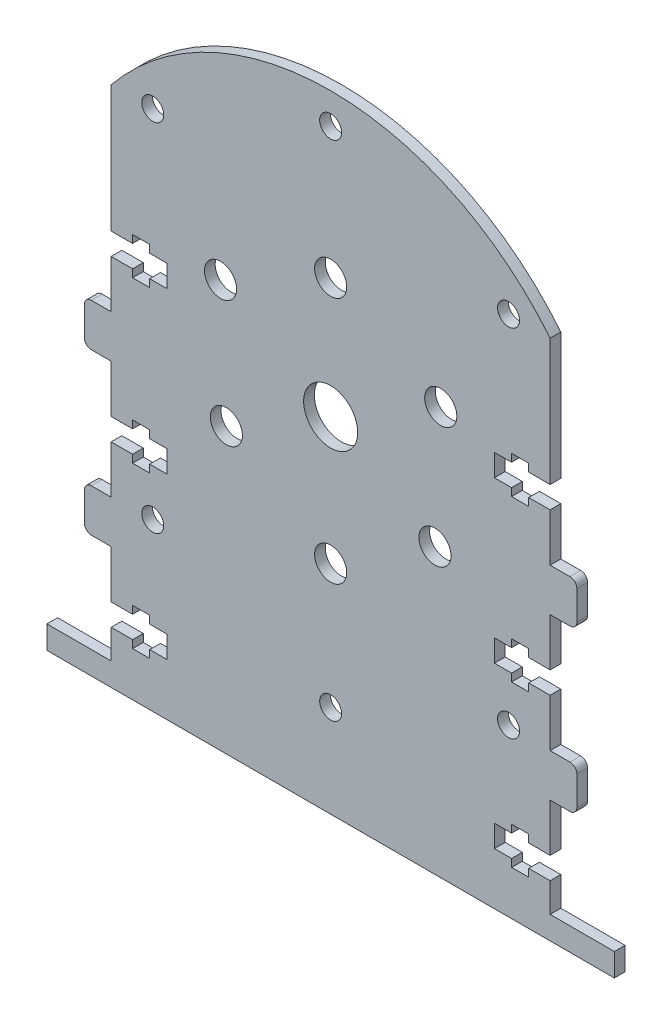
SolidWorks part; units mm, degrees
ref_plane "前视基准面" through (0, 0, 0) normal (0, 0, 1) x (1, 0, 0)
ref_plane "上视基准面" through (0, 0, 0) normal (0, 1, 0) x (1, 0, 0)
ref_plane "右视基准面" through (0, 0, 0) normal (1, 0, 0) x (0, 0, -1)
sketch "草图1" plane through (0, 0, 0) normal (0, 0, 1) x (1, 0, 0)
  line L0 (-14.9625, -1.5035) -> (21.2348, -1.5035) construction
  line L1 (-14.9625, -1.5035) -> (24.3099, -24.1774) construction
  line L2 (-14.9625, -25.2535) -> (-14.9625, -1.5035) construction
  line L3 (26.0375, -61.5035) -> (-55.9625, -61.5035) construction
  line L4 (26.0375, -61.5035) -> (26.0375, 58.4965) construction
  line L5 (26.0375, 58.4965) -> (-55.9625, 58.4965) construction
  line L7 (26.0375, -61.5035) -> (-55.9625, 58.4965) construction
  line L8 (26.0375, 58.4965) -> (-55.9625, -61.5035) construction
  line L9 (-14.9625, -1.5035) -> (-98.8628, 46.9364) construction
  line L10 (-14.9625, -1.5035) -> (68.9378, 46.9364) construction
  line L11 (-58.2638, 23.4965) -> (-55.9625, 23.4965) construction
  line L12 (-55.9625, 23.4965) -> (-55.9625, 8.0465)
  line L13 (-55.9625, 8.0465) -> (-51.9625, 8.0465)
  line L14 (-51.9625, 8.0465) -> (-51.9625, 9.4965)
  line L15 (-51.9625, 9.4965) -> (-48.7625, 9.4965)
  line L16 (-48.7625, 9.4965) -> (-48.7625, 8.0465)
  line L17 (-48.7625, 8.0465) -> (-45.5625, 8.0465)
  line L18 (-45.5625, 8.0465) -> (-45.5625, 3.9465)
  line L19 (-45.5625, 3.9465) -> (-48.7625, 3.9465)
  line L20 (-48.7625, 3.9465) -> (-48.7625, 2.4965)
  line L21 (-48.7625, 2.4965) -> (-51.9625, 2.4965)
  line L22 (-51.9625, 2.4965) -> (-51.9625, 3.9465)
  line L23 (-51.9625, 3.9465) -> (-55.9625, 3.9465)
  line L24 (-55.9625, -5.0035) -> (-60.9625, -5.0035)
  line L25 (-60.9625, -5.0035) -> (-60.9625, -13.0035)
  line L26 (-60.9625, -13.0035) -> (-55.9625, -13.0035)
  line L27 (-60.9625, -9.0035) -> (-58.1553, -9.0035) construction
  line L28 (-51.9625, -21.9535) -> (-55.9625, -21.9535)
  line L29 (-51.9625, -20.5035) -> (-51.9625, -21.9535)
  line L30 (-48.7625, -20.5035) -> (-51.9625, -20.5035)
  line L31 (-48.7625, -21.9535) -> (-48.7625, -20.5035)
  line L32 (-45.5625, -21.9535) -> (-48.7625, -21.9535)
  line L33 (-45.5625, -26.0535) -> (-45.5625, -21.9535)
  line L34 (-48.7625, -26.0535) -> (-45.5625, -26.0535)
  line L35 (-48.7625, -27.5035) -> (-48.7625, -26.0535)
  line L36 (-51.9625, -27.5035) -> (-48.7625, -27.5035)
  line L37 (-51.9625, -26.0535) -> (-51.9625, -27.5035)
  line L38 (-55.9625, -26.0535) -> (-51.9625, -26.0535)
  line L39 (-55.9625, -21.9535) -> (-55.9625, -13.0035)
  line L40 (-45.5625, -24.0035) -> (-48.2625, -24.0035) construction
  line L41 (-55.9625, -43.0035) -> (-60.9625, -43.0035)
  line L42 (-60.9625, -43.0035) -> (-60.9625, -35.0035)
  line L43 (-60.9625, -35.0035) -> (-55.9625, -35.0035)
  line L44 (-60.9625, -39.0035) -> (-57.1747, -39.0035) construction
  line L45 (-45.5625, -54.0035) -> (-48.2625, -54.0035) construction
  line L46 (-55.9625, 3.9465) -> (-55.9625, -5.0035)
  line L47 (-55.9625, -26.0535) -> (-55.9625, -35.0035)
  line L48 (-55.9625, -51.9535) -> (-51.9625, -51.9535)
  line L49 (-51.9625, -51.9535) -> (-51.9625, -50.5035)
  line L50 (-51.9625, -50.5035) -> (-48.7625, -50.5035)
  line L51 (-48.7625, -50.5035) -> (-48.7625, -51.9535)
  line L52 (-48.7625, -51.9535) -> (-45.5625, -51.9535)
  line L53 (-45.5625, -51.9535) -> (-45.5625, -56.0535)
  line L54 (-45.5625, -56.0535) -> (-48.7625, -56.0535)
  line L55 (-48.7625, -56.0535) -> (-48.7625, -57.5035)
  line L56 (-48.7625, -57.5035) -> (-51.9625, -57.5035)
  line L57 (-51.9625, -57.5035) -> (-51.9625, -56.0535)
  line L58 (-51.9625, -56.0535) -> (-55.9625, -56.0535)
  line L59 (-55.9625, -43.0035) -> (-55.9625, -51.9535)
  line L60 (-55.9625, -56.0535) -> (-55.9625, -61.5035)
  line L61 (15.6375, -54.0035) -> (18.3375, -54.0035) construction
  line L62 (31.0375, -39.0035) -> (27.2497, -39.0035) construction
  line L63 (15.6375, -24.0035) -> (18.3375, -24.0035) construction
  line L64 (31.0375, -9.0035) -> (28.2303, -9.0035) construction
  line L65 (26.0375, -43.0035) -> (26.0375, -51.9535)
  line L66 (22.0375, -56.0535) -> (26.0375, -56.0535)
  line L67 (22.0375, -57.5035) -> (22.0375, -56.0535)
  line L68 (18.8375, -57.5035) -> (22.0375, -57.5035)
  line L69 (18.8375, -56.0535) -> (18.8375, -57.5035)
  line L70 (15.6375, -56.0535) -> (18.8375, -56.0535)
  line L71 (15.6375, -51.9535) -> (15.6375, -56.0535)
  line L72 (18.8375, -51.9535) -> (15.6375, -51.9535)
  line L73 (18.8375, -50.5035) -> (18.8375, -51.9535)
  line L74 (22.0375, -50.5035) -> (18.8375, -50.5035)
  line L75 (22.0375, -51.9535) -> (22.0375, -50.5035)
  line L76 (26.0375, -51.9535) -> (22.0375, -51.9535)
  line L77 (26.0375, -26.0535) -> (26.0375, -35.0035)
  line L78 (26.0375, 3.9465) -> (26.0375, -5.0035)
  line L79 (31.0375, -35.0035) -> (26.0375, -35.0035)
  line L80 (31.0375, -43.0035) -> (31.0375, -35.0035)
  line L81 (26.0375, -43.0035) -> (31.0375, -43.0035)
  line L82 (26.0375, -21.9535) -> (26.0375, -13.0035)
  line L83 (26.0375, -26.0535) -> (22.0375, -26.0535)
  line L84 (22.0375, -26.0535) -> (22.0375, -27.5035)
  line L85 (22.0375, -27.5035) -> (18.8375, -27.5035)
  line L86 (18.8375, -27.5035) -> (18.8375, -26.0535)
  line L87 (18.8375, -26.0535) -> (15.6375, -26.0535)
  line L88 (15.6375, -26.0535) -> (15.6375, -21.9535)
  line L89 (15.6375, -21.9535) -> (18.8375, -21.9535)
  line L90 (18.8375, -21.9535) -> (18.8375, -20.5035)
  line L91 (18.8375, -20.5035) -> (22.0375, -20.5035)
  line L92 (22.0375, -20.5035) -> (22.0375, -21.9535)
  line L93 (22.0375, -21.9535) -> (26.0375, -21.9535)
  line L94 (31.0375, -13.0035) -> (26.0375, -13.0035)
  line L95 (31.0375, -5.0035) -> (31.0375, -13.0035)
  line L96 (26.0375, -5.0035) -> (31.0375, -5.0035)
  line L97 (22.0375, 3.9465) -> (26.0375, 3.9465)
  line L98 (22.0375, 2.4965) -> (22.0375, 3.9465)
  line L99 (18.8375, 2.4965) -> (22.0375, 2.4965)
  line L100 (18.8375, 3.9465) -> (18.8375, 2.4965)
  line L101 (15.6375, 3.9465) -> (18.8375, 3.9465)
  line L102 (15.6375, 8.0465) -> (15.6375, 3.9465)
  line L103 (18.8375, 8.0465) -> (15.6375, 8.0465)
  line L104 (18.8375, 9.4965) -> (18.8375, 8.0465)
  line L105 (22.0375, 9.4965) -> (18.8375, 9.4965)
  line L106 (22.0375, 8.0465) -> (22.0375, 9.4965)
  line L107 (26.0375, 8.0465) -> (22.0375, 8.0465)
  line L108 (26.0375, 23.4965) -> (26.0375, 8.0465)
  line L109 (28.3388, 23.4965) -> (26.0375, 23.4965) construction
  line L110 (26.0375, -56.0535) -> (26.0375, -61.5035)
  line L115 (-55.9625, 23.4965) -> (-55.9625, 31.723)
  line L116 (26.0375, 23.4965) -> (26.0375, 31.723)
  line L117 (-45.5625, 5.9965) -> (-55.9625, 5.9965) construction
  line L118 (-67.9625, -65.7919) -> (38.0375, -65.7919)
  line L125 (-55.9625, -61.5035) -> (-67.9625, -61.5035)
  line L126 (-67.9625, -61.5035) -> (-67.9625, -65.7919)
  line L127 (26.0375, -61.5035) -> (38.0375, -61.5035)
  line L128 (38.0375, -61.5035) -> (38.0375, -65.7919)
  circle A0 centre (-14.9625, -1.5035) radius 23.75 construction
  circle A1 centre (-14.9625, -1.5035) radius 22.5 construction
  circle A2 centre (-14.9625, -25.2535) radius 3
  circle A5 centre (4.5231, -12.7535) radius 3
  circle A8 centre (-14.9625, -1.5035) radius 5.05
  circle A15 centre (-14.9625, -1.5035) radius 47 construction
  circle A17 centre (-35.5306, 10.3715) radius 3
  circle A18 centre (-34.4481, -12.7535) radius 3
  circle A19 centre (5.6056, 10.3715) radius 3
  circle A20 centre (-14.9625, 20.9965) radius 3
  circle A21 centre (32.0375, -1.5035) radius 2.05 construction
  circle A22 centre (18.2715, -34.7375) radius 2.05
  circle A23 centre (-14.9625, -48.5035) radius 2.05
  circle A24 centre (-48.1965, -34.7375) radius 2.05
  circle A25 centre (-61.9625, -1.5035) radius 2.05 construction
  circle A26 centre (-48.1965, 31.7305) radius 2.05
  circle A27 centre (-14.9625, 45.4965) radius 2.05
  circle A28 centre (18.2715, 31.7305) radius 2.05
  circle A31 centre (-14.9625, -1.5035) radius 52.7731 construction
  arc A34 (-55.9625, 31.723) -> (26.0375, 31.723) centre (-14.9625, -1.5035) cw
  point P41 (-54.9625, -9.0035)
  point P135 (25.0375, -9.0035)
  dimension "D1" = 47.5
  dimension "D2" = 45
  dimension "D3" = 6
  dimension "D5" = 6
  dimension "D18" = 60
  dimension "D19" = 8
  dimension "D20" = 10.1
  dimension "D21" = 94
  dimension "D22" = 12
  dimension "D23" = 12
  dimension "D4" = 30
  dimension "D6" = 82
  dimension "D8" = 120
  dimension "D9" = 4.1
  dimension "D10" = 3.2
  dimension "D11" = 7
  dimension "D12" = 4
  dimension "D13" = 14
  dimension "D14" = 15
  dimension "D15" = 8
  dimension "D16" = 5
  dimension "D17" = 4
  dimension "D7" = 3
extrude "凸台-拉伸2" add sketch "草图1" along normal blind 2
sketch "草图2" plane through (-55.9625, 0, 0) normal (-1, 0, 0) x (0, 0, 1)
  line L0 (1, -56.0535) -> (1, -51.9535)
  line L1 (2, -56.0535) -> (0, -56.0535) construction
  line L2 (2, -51.9535) -> (0, -51.9535) construction
  circle A0 centre (1, -54.0035) radius 2.05
sketch "草图3" plane through (26.0375, 0, 0) normal (1, 0, 0) x (0, 0, -1)
  line L0 (-1, -51.9535) -> (-1, -56.0535)
  line L1 (-2, -51.9535) -> (0, -51.9535) construction
  line L2 (-2, -56.0535) -> (0, -56.0535) construction
  circle A0 centre (-1, -54.0035) radius 2.05
fillet "圆角1" radius 1.3 8 edges at (-60.9625, -5.0035, 1) (-60.9625, -35.0035, 1) (-60.9625, -13.0035, 1) (-60.9625, -43.0035, 1) (31.0375, -43.0035, 1) (31.0375, -35.0035, 1) (31.0375, -5.0035, 1) (31.0375, -13.0035, 1)
